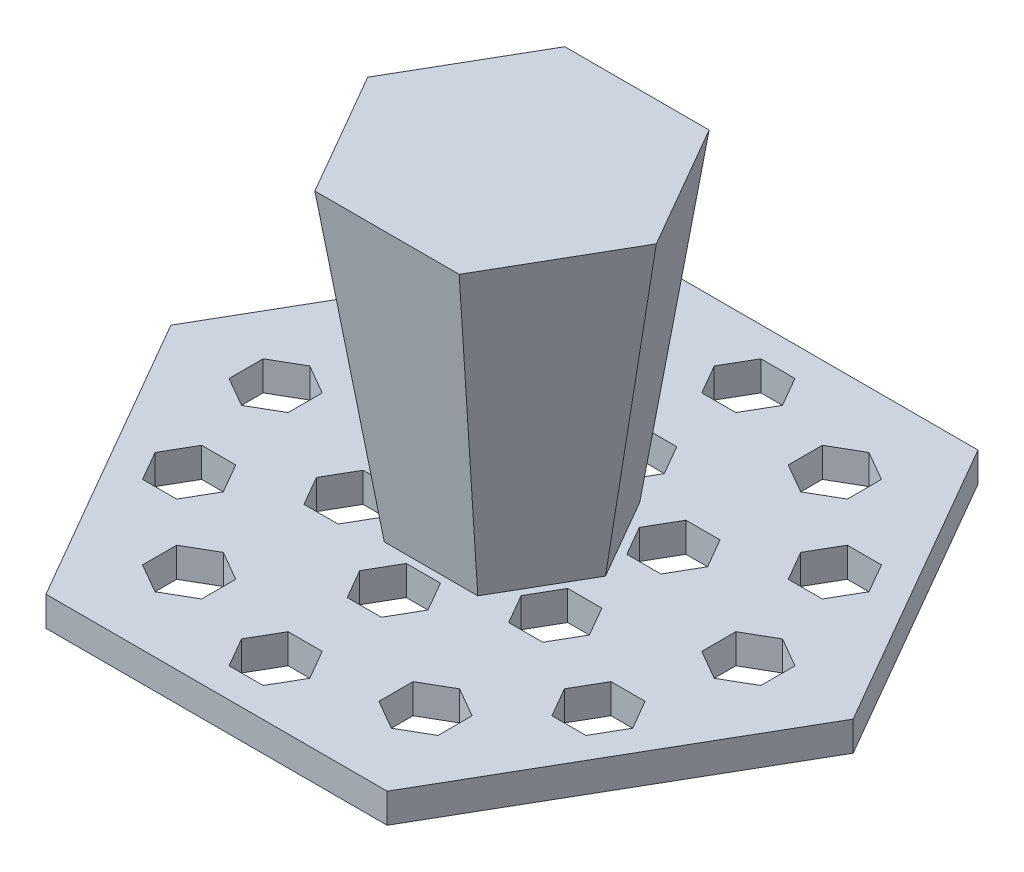
SolidWorks part; units mm, degrees
ref_plane "Front Plane" through (0, 0, 0) normal (0, 0, 1) x (1, 0, 0)
ref_plane "Top Plane" through (0, 0, 0) normal (0, 1, 0) x (1, 0, 0)
ref_plane "Right Plane" through (0, 0, 0) normal (1, 0, 0) x (0, 0, -1)
sketch "Sketch1" plane through (0, 0, 0) normal (0, 1, 0) x (1, 0, 0)
  line L0 (25, 37.5278) -> (20, 40.4145)
  line L1 (28.8675, 50) -> (-28.8675, 50)
  line L2 (-28.8675, 50) -> (-57.735, 0)
  line L3 (-57.735, 0) -> (-28.8675, -50)
  line L4 (-28.8675, -50) -> (28.8675, -50)
  line L5 (28.8675, -50) -> (57.735, 0)
  line L6 (57.735, 0) -> (28.8675, 50)
  line L7 (2.8868, 45) -> (-2.8868, 45)
  line L8 (-2.8868, 45) -> (-5.7735, 40)
  line L9 (-5.7735, 40) -> (-2.8868, 35)
  line L10 (-2.8868, 35) -> (2.8868, 35)
  line L11 (2.8868, 35) -> (5.7735, 40)
  line L12 (5.7735, 40) -> (2.8868, 45)
  line L13 (20, 40.4145) -> (15, 37.5278)
  line L14 (15, 37.5278) -> (15, 31.7543)
  line L15 (15, 31.7543) -> (20, 28.8675)
  line L16 (20, 28.8675) -> (25, 31.7543)
  line L17 (25, 31.7543) -> (25, 37.5278)
  line L18 (40.4145, 20) -> (37.5278, 25)
  line L19 (37.5278, 25) -> (31.7543, 25)
  line L20 (31.7543, 25) -> (28.8675, 20)
  line L21 (28.8675, 20) -> (31.7543, 15)
  line L22 (31.7543, 15) -> (37.5278, 15)
  line L23 (37.5278, 15) -> (40.4145, 20)
  line L24 (45, -2.8868) -> (45, 2.8868)
  line L25 (45, 2.8868) -> (40, 5.7735)
  line L26 (40, 5.7735) -> (35, 2.8868)
  line L27 (35, 2.8868) -> (35, -2.8868)
  line L28 (35, -2.8868) -> (40, -5.7735)
  line L29 (40, -5.7735) -> (45, -2.8868)
  line L30 (37.5278, -25) -> (40.4145, -20)
  line L31 (40.4145, -20) -> (37.5278, -15)
  line L32 (37.5278, -15) -> (31.7543, -15)
  line L33 (31.7543, -15) -> (28.8675, -20)
  line L34 (28.8675, -20) -> (31.7543, -25)
  line L35 (31.7543, -25) -> (37.5278, -25)
  line L36 (20, -40.4145) -> (25, -37.5278)
  line L37 (25, -37.5278) -> (25, -31.7543)
  line L38 (25, -31.7543) -> (20, -28.8675)
  line L39 (20, -28.8675) -> (15, -31.7543)
  line L40 (15, -31.7543) -> (15, -37.5278)
  line L41 (15, -37.5278) -> (20, -40.4145)
  line L114 (20.2073, 5) -> (23.094, 10)
  line L115 (5.7735, 20) -> (2.8868, 25)
  line L116 (2.8868, 25) -> (-2.8868, 25)
  line L117 (-2.8868, 25) -> (-5.7735, 20)
  line L118 (-5.7735, 20) -> (-2.8868, 15)
  line L119 (-2.8868, 15) -> (2.8868, 15)
  line L120 (2.8868, 15) -> (5.7735, 20)
  line L121 (23.094, 10) -> (20.2073, 15)
  line L122 (20.2073, 15) -> (14.4338, 15)
  line L123 (14.4338, 15) -> (11.547, 10)
  line L124 (11.547, 10) -> (14.4338, 5)
  line L125 (14.4338, 5) -> (20.2073, 5)
  line L126 (14.4338, -15) -> (20.2073, -15)
  line L127 (20.2073, -15) -> (23.094, -10)
  line L128 (23.094, -10) -> (20.2073, -5)
  line L129 (20.2073, -5) -> (14.4338, -5)
  line L130 (14.4338, -5) -> (11.547, -10)
  line L131 (11.547, -10) -> (14.4338, -15)
  line L132 (-5.7735, -20) -> (-2.8868, -25)
  line L133 (-2.8868, -25) -> (2.8868, -25)
  line L134 (2.8868, -25) -> (5.7735, -20)
  line L135 (5.7735, -20) -> (2.8868, -15)
  line L136 (2.8868, -15) -> (-2.8868, -15)
  line L137 (-2.8868, -15) -> (-5.7735, -20)
  line L138 (-20.2073, -5) -> (-23.094, -10)
  line L139 (-23.094, -10) -> (-20.2073, -15)
  line L140 (-20.2073, -15) -> (-14.4338, -15)
  line L141 (-14.4338, -15) -> (-11.547, -10)
  line L142 (-11.547, -10) -> (-14.4338, -5)
  line L143 (-14.4338, -5) -> (-20.2073, -5)
  line L144 (-14.4338, 15) -> (-20.2073, 15)
  line L145 (-20.2073, 15) -> (-23.094, 10)
  line L146 (-23.094, 10) -> (-20.2073, 5)
  line L147 (-20.2073, 5) -> (-14.4338, 5)
  line L148 (-14.4338, 5) -> (-11.547, 10)
  line L149 (-11.547, 10) -> (-14.4338, 15)
  line L150 (-2.8868, -45) -> (2.8868, -45)
  line L151 (2.8868, -45) -> (5.7735, -40)
  line L152 (5.7735, -40) -> (2.8868, -35)
  line L153 (2.8868, -35) -> (-2.8868, -35)
  line L154 (-2.8868, -35) -> (-5.7735, -40)
  line L155 (-5.7735, -40) -> (-2.8868, -45)
  line L156 (-25, -37.5278) -> (-20, -40.4145)
  line L157 (-20, -40.4145) -> (-15, -37.5278)
  line L158 (-15, -37.5278) -> (-15, -31.7543)
  line L159 (-15, -31.7543) -> (-20, -28.8675)
  line L160 (-20, -28.8675) -> (-25, -31.7543)
  line L161 (-25, -31.7543) -> (-25, -37.5278)
  line L162 (-40.4145, -20) -> (-37.5278, -25)
  line L163 (-37.5278, -25) -> (-31.7543, -25)
  line L164 (-31.7543, -25) -> (-28.8675, -20)
  line L165 (-28.8675, -20) -> (-31.7543, -15)
  line L166 (-31.7543, -15) -> (-37.5278, -15)
  line L167 (-37.5278, -15) -> (-40.4145, -20)
  line L168 (-45, 2.8868) -> (-45, -2.8868)
  line L169 (-45, -2.8868) -> (-40, -5.7735)
  line L170 (-40, -5.7735) -> (-35, -2.8868)
  line L171 (-35, -2.8868) -> (-35, 2.8868)
  line L172 (-35, 2.8868) -> (-40, 5.7735)
  line L173 (-40, 5.7735) -> (-45, 2.8868)
  line L174 (-37.5278, 25) -> (-40.4145, 20)
  line L175 (-40.4145, 20) -> (-37.5278, 15)
  line L176 (-37.5278, 15) -> (-31.7543, 15)
  line L177 (-31.7543, 15) -> (-28.8675, 20)
  line L178 (-28.8675, 20) -> (-31.7543, 25)
  line L179 (-31.7543, 25) -> (-37.5278, 25)
  line L180 (-20, 40.4145) -> (-25, 37.5278)
  line L181 (-25, 37.5278) -> (-25, 31.7543)
  line L182 (-25, 31.7543) -> (-20, 28.8675)
  line L183 (-20, 28.8675) -> (-15, 31.7543)
  line L184 (-15, 31.7543) -> (-15, 37.5278)
  line L185 (-15, 37.5278) -> (-20, 40.4145)
  line L186 (-41.9257, -24.2058) -> (64.3034, 37.1256) construction
  line L187 (44.0241, -25.4173) -> (-59.8989, 34.5827) construction
  line L188 (0, 40) -> (0, -20) construction
  line L189 (-47.6314, 47.5) -> (-64.9519, 47.5)
  line L190 (-64.9519, 47.5) -> (-73.6122, 32.5)
  line L191 (-73.6122, 32.5) -> (-64.9519, 17.5)
  line L192 (-64.9519, 17.5) -> (-47.6314, 17.5)
  line L193 (-47.6314, 17.5) -> (-38.9711, 32.5)
  line L194 (-38.9711, 32.5) -> (-47.6314, 47.5)
  line L195 (38.9711, 32.5) -> (47.6314, 47.5)
  line L196 (47.6314, 17.5) -> (38.9711, 32.5)
  line L197 (64.9519, 17.5) -> (47.6314, 17.5)
  line L198 (73.6122, 32.5) -> (64.9519, 17.5)
  line L199 (64.9519, 47.5) -> (73.6122, 32.5)
  line L200 (47.6314, 47.5) -> (64.9519, 47.5)
  line L201 (0, 0) -> (57.735, 0) construction
  line L202 (-38.9711, -32.5) -> (-47.6314, -47.5)
  line L203 (-47.6314, -17.5) -> (-38.9711, -32.5)
  line L204 (-64.9519, -17.5) -> (-47.6314, -17.5)
  line L205 (-73.6122, -32.5) -> (-64.9519, -17.5)
  line L206 (-64.9519, -47.5) -> (-73.6122, -32.5)
  line L207 (-47.6314, -47.5) -> (-64.9519, -47.5)
  line L208 (47.6314, -17.5) -> (38.9711, -32.5)
  line L209 (64.9519, -17.5) -> (47.6314, -17.5)
  line L210 (73.6122, -32.5) -> (64.9519, -17.5)
  line L211 (64.9519, -47.5) -> (73.6122, -32.5)
  line L212 (47.6314, -47.5) -> (64.9519, -47.5)
  line L213 (38.9711, -32.5) -> (47.6314, -47.5)
  line L214 (0, 50) -> (0, 85.872) construction
  line L215 (8.6603, -50) -> (17.3205, -65)
  line L216 (17.3205, 65) -> (8.6603, 80)
  line L217 (8.6603, 80) -> (-8.6603, 80)
  line L218 (-8.6603, 80) -> (-17.3205, 65)
  line L219 (-17.3205, 65) -> (-8.6603, 50)
  line L220 (-8.6603, 50) -> (8.6603, 50)
  line L221 (8.6603, 50) -> (17.3205, 65)
  line L222 (-8.6603, -50) -> (8.6603, -50)
  line L223 (-17.3205, -65) -> (-8.6603, -50)
  line L224 (-8.6603, -80) -> (-17.3205, -65)
  line L225 (8.6603, -80) -> (-8.6603, -80)
  line L226 (17.3205, -65) -> (8.6603, -80)
  circle A0 centre (0, 0) radius 50 construction
  circle A1 centre (0, 0) radius 40 construction
  circle A2 centre (0, 40) radius 5 construction
  circle A3 centre (0, 0) radius 20 construction
  circle A4 centre (0, 20) radius 5 construction
  circle A5 centre (-56.2917, 32.5) radius 15 construction
  circle A6 centre (0, 65) radius 15 construction
  point P120 (0, 0)
  point P123 (0, 0)
  point P163 (0, 0)
  point P167 (0, 0)
  point P174 (43.3013, 25)
  dimension "D1" = 100
  dimension "D2" = 80
  dimension "D3" = 10
  dimension "D5" = 40
  dimension "D6" = 6
  dimension "D7" = 30
  dimension "D4" = 12
extrude "Boss-Extrude1" add sketch "Sketch1" along normal blind 5 contours L5 L6 L1 L2 L3 L4 L185 L184 L183 L182 L181 L180 L179 L178 L177 L176 L175 L174 L173 L172 L171 L170 L169 L168 L167 L166 L165 L164 L163 L162 L161 L160 L159 L158
sketch "Sketch2" plane through (0, 0, 0) normal (0, 1, 0) x (1, 0, 0)
  line L0 (0, 50) -> (0, -50) construction
  line L1 (7.5056, 13) -> (-7.5056, 13)
  line L2 (-7.5056, 13) -> (-15.0111, 0)
  line L3 (-15.0111, 0) -> (-7.5056, -13)
  line L4 (-7.5056, -13) -> (7.5056, -13)
  line L5 (7.5056, -13) -> (15.0111, 0)
  line L6 (15.0111, 0) -> (7.5056, 13)
  line L7 (29.4641, 6) -> (22.5359, 6)
  line L8 (22.5359, 6) -> (19.0718, 0)
  line L9 (19.0718, 0) -> (22.5359, -6)
  line L10 (22.5359, -6) -> (29.4641, -6)
  line L11 (29.4641, -6) -> (32.9282, 0)
  line L12 (32.9282, 0) -> (29.4641, 6)
  line L13 (28.8675, 50) -> (-28.8675, 50) construction
  line L14 (-28.8675, -50) -> (28.8675, -50) construction
  line L15 (-32.9282, 0) -> (-29.4641, 6)
  line L16 (-29.4641, -6) -> (-32.9282, 0)
  line L17 (-22.5359, -6) -> (-29.4641, -6)
  line L18 (-19.0718, 0) -> (-22.5359, -6)
  line L19 (-22.5359, 6) -> (-19.0718, 0)
  line L20 (-29.4641, 6) -> (-22.5359, 6)
  circle A0 centre (0, 0) radius 13 construction
  circle A1 centre (26, 0) radius 6 construction
  point P23 (0, 0)
  dimension "D1" = 26
  dimension "D2" = 12
  dimension "D3" = 26
extrude "Boss-Extrude2" add sketch "Sketch2" along normal blind 58 draft 8 contours L5 L6 L1 L2 L3 L4 draft outward yes
sketch "Sketch3" plane through (0, 58, 0) normal (0, 1, 0) x (1, 0, 0)
  line L0 (0, -10.5547) -> (0, 35.8587) construction
  line L1 (12.2117, 21.1514) -> (-12.2117, 21.1514) construction
  line L2 (5.7735, 21.1514) -> (11.547, 31.1514)
  line L3 (11.547, 31.1514) -> (5.7735, 41.1514)
  line L4 (5.7735, 41.1514) -> (-5.7735, 41.1514)
  line L5 (-5.7735, 41.1514) -> (-11.547, 31.1514)
  line L6 (-11.547, 31.1514) -> (-5.7735, 21.1514)
  line L7 (-5.7735, 21.1514) -> (5.7735, 21.1514)
  line L8 (21.2044, 5.5757) -> (32.7514, 5.5757)
  line L9 (32.7514, 5.5757) -> (38.5249, 15.5757)
  line L10 (38.5249, 15.5757) -> (32.7514, 25.5757)
  line L11 (32.7514, 25.5757) -> (21.2044, 25.5757)
  line L12 (21.2044, 25.5757) -> (15.4309, 15.5757)
  line L13 (15.4309, 15.5757) -> (21.2044, 5.5757)
  line L14 (15.4309, -15.5757) -> (21.2044, -25.5757)
  line L15 (21.2044, -25.5757) -> (32.7514, -25.5757)
  line L16 (32.7514, -25.5757) -> (38.5249, -15.5757)
  line L17 (38.5249, -15.5757) -> (32.7514, -5.5757)
  line L18 (32.7514, -5.5757) -> (21.2044, -5.5757)
  line L19 (21.2044, -5.5757) -> (15.4309, -15.5757)
  line L20 (-5.7735, -21.1514) -> (-11.547, -31.1514)
  line L21 (-11.547, -31.1514) -> (-5.7735, -41.1514)
  line L22 (-5.7735, -41.1514) -> (5.7735, -41.1514)
  line L23 (5.7735, -41.1514) -> (11.547, -31.1514)
  line L24 (11.547, -31.1514) -> (5.7735, -21.1514)
  line L25 (5.7735, -21.1514) -> (-5.7735, -21.1514)
  line L26 (-21.2044, -5.5757) -> (-32.7514, -5.5757)
  line L27 (-32.7514, -5.5757) -> (-38.5249, -15.5757)
  line L28 (-38.5249, -15.5757) -> (-32.7514, -25.5757)
  line L29 (-32.7514, -25.5757) -> (-21.2044, -25.5757)
  line L30 (-21.2044, -25.5757) -> (-15.4309, -15.5757)
  line L31 (-15.4309, -15.5757) -> (-21.2044, -5.5757)
  line L32 (-15.4309, 15.5757) -> (-21.2044, 25.5757)
  line L33 (-21.2044, 25.5757) -> (-32.7514, 25.5757)
  line L34 (-32.7514, 25.5757) -> (-38.5249, 15.5757)
  line L35 (-38.5249, 15.5757) -> (-32.7514, 5.5757)
  line L36 (-32.7514, 5.5757) -> (-21.2044, 5.5757)
  line L37 (-21.2044, 5.5757) -> (-15.4309, 15.5757)
  circle A0 centre (0, 31.1514) radius 10 construction
  point P15 (0, 0)
  point P46 (0, 0)
  dimension "D1" = 20
  dimension "D2" = 6
sketch "Sketch4" plane through (0, 0, 0) normal (1, 0, 0) x (0, 0, -1)
  line L0 (65, 0) -> (31.1514, 58)
  line L1 (65, 0) -> (50, 0) construction
  line L2 (80, 0) -> (65, 0) construction
  point P7 (79.8512, 0)
